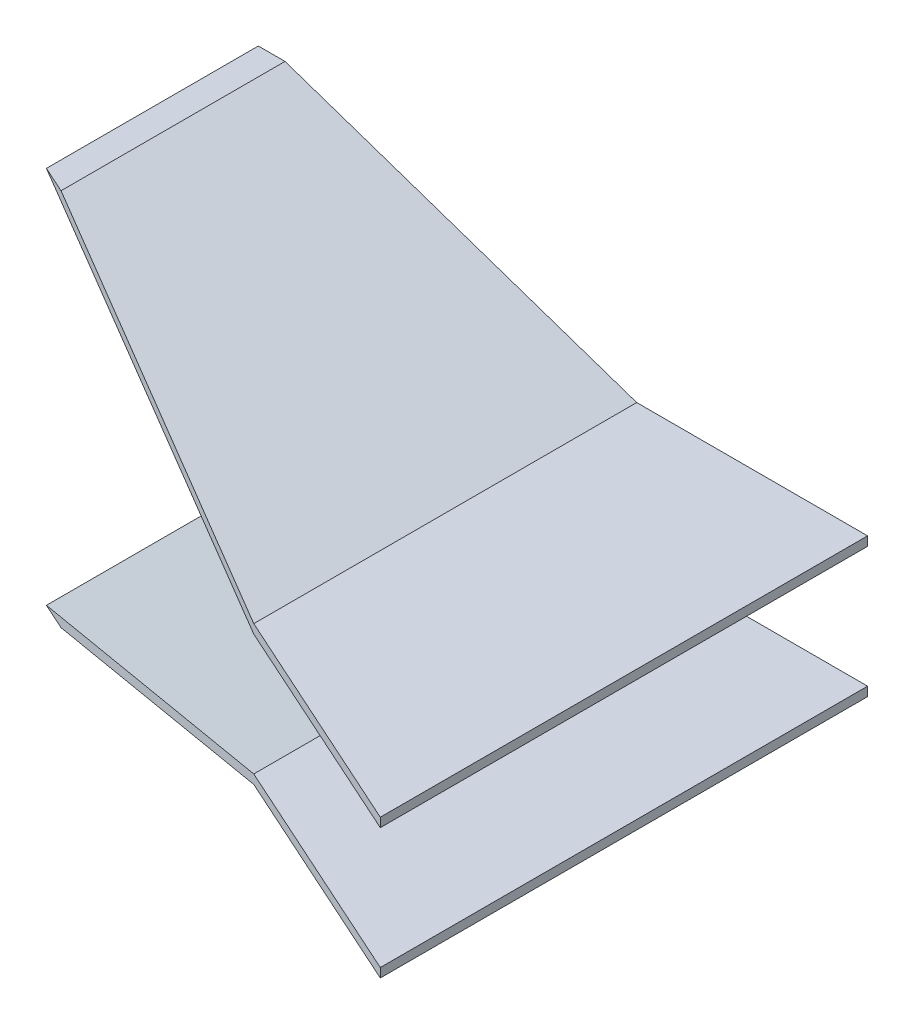
SolidWorks part; units mm, degrees
ref_plane "Plano frontal" through (0, 0, 0) normal (0, 0, 1) x (1, 0, 0)
ref_plane "Plano superior" through (0, 0, 0) normal (0, 1, 0) x (1, 0, 0)
ref_plane "Plano direito" through (0, 0, 0) normal (1, 0, 0) x (0, 0, -1)
sketch "Esboço1" plane through (0, 0, 0) normal (0, 0, 1) x (1, 0, 0)
  line L1 (0, 0) -> (6, 0)
  line L2 (0, 0) -> (0, -250)
  line L3 (0, -250) -> (6, -250)
  line L4 (6, 0) -> (6, -250)
extrude "Ressalto-extrusão1" add sketch "Esboço1" along normal blind 140
sketch "Esboço3" plane through (0, 0, 0) normal (0, 1, 0) x (1, 0, 0)
  line L0 (6, -140) -> (256, -253)
  line L1 (6, -140) -> (256, -140)
  line L2 (256, -140) -> (256, -253)
extrude "Ressalto-extrusão2" add sketch "Esboço3" against normal blind 250 separate body
sketch "Esboço5" plane through (0, 0, 140) normal (0, 0, -1) x (-1, 0, 0)
  line L0 (-256, 0) -> (-256, -250) construction
  line L3 (-256, -85) -> (-6, 0)
  line L8 (-6, -250) -> (-256, -165)
  line L9 (-6, 0) -> (-6, -250)
  line L12 (-256, -165) -> (-256, -85)
extrude "Corte-extrusão2" cut sketch "Esboço5" against normal through all
sketch "Esboço6" plane through (0, 0, 140) normal (0, 0, -1) x (-1, 0, 0)
  line L0 (-256, -85) -> (-256, -79)
  line L1 (-256, -85) -> (-256, 0) construction
  line L3 (-256, -171) -> (-256, -250)
  line L5 (-256, 0) -> (-256, -79)
  line L6 (-256, -250) -> (-256, -165) construction
  line L7 (-256, -250) -> (-6, -250) construction
  line L8 (-256, -79) -> (-23.6471, 0)
  line L9 (-256, -250) -> (-6, -250)
  line L10 (-23.6471, 0) -> (-256, 0)
  line L11 (-256, 0) -> (-6, 0) construction
  line L13 (-256, -171) -> (-23.6471, -250)
  line L15 (-256, -250) -> (-23.6471, -250)
  line M11 (-6, 0) -> (-256, 0)
  line M12 (-256, 0) -> (-256, -85)
  dimension "D1" = 6
  dimension "D2" = 6
extrude "Corte-extrusão3" cut sketch "Esboço6" against normal through all contours L8 M12 M11 | L13 L3 L9
sketch "Esboço7" plane through (6, 0, 0) normal (1, 0, 0) x (0, 0, -1)
  line L0 (-140, -79) -> (-140, 0) construction
  line L1 (0, 0) -> (-140, 0)
  line L2 (0, 0) -> (0, -250)
  line L3 (0, -250) -> (-140, -250)
  line L4 (-140, 0) -> (-140, -250)
sketch "Esboço8" plane through (0, 0, 140) normal (0, 0, -1) x (-1, 0, 0)
  line L0 (-256, -79) -> (-23.6471, 0)
  line L1 (-23.6471, 0) -> (-6, 0)
  line L2 (-6, 0) -> (-6, -250) construction
  line L3 (-6, 0) -> (-256, -85) construction
  line L4 (-6, 0) -> (-256, -85)
  line L5 (-256, -85) -> (-256, -79)
  line L6 (-256, -165) -> (-256, -171)
  line L7 (-256, -171) -> (-23.6471, -250)
  line L8 (-23.6471, -250) -> (-6, -250)
  line L9 (-6, -250) -> (-256, -165)
extrude "Ressalto-extrusão3" add sketch "Esboço8" along normal blind 140
sketch "Esboço9" plane through (6, 0, 0) normal (1, 0, 0) x (0, 0, -1)
extrude "Corte-extrusão4" cut sketch "Esboço7" against normal through all
sketch "Esboço11" plane through (-51.527, 0, 113.9978) normal (-0.4119, 0, 0.9112) x (0.9112, 0, 0.4119)
  line L0 (337.4825, -85) -> (504.8825, -85)
  line L1 (337.4825, -79) -> (504.8825, -79)
  line L2 (337.4825, -85) -> (337.4825, -79) construction
  line L3 (82.4966, 0) -> (337.4825, -79) construction
  line L4 (504.8825, -79) -> (504.8825, -85)
  line L6 (337.4825, -165) -> (504.8825, -165)
  line L8 (337.4825, -171) -> (504.8825, -171)
  line L9 (504.8825, -171) -> (504.8825, -165)
  line L10 (337.4825, -85) -> (201.906, -42.9955)
  line L11 (337.4825, -85) -> (63.1306, 0) construction
  line L12 (201.906, -42.9955) -> (203.6021, -37.521)
  line L13 (203.6021, -37.521) -> (337.4825, -79)
  line L14 (337.4825, -171) -> (181.315, -219.384)
  line L15 (82.4966, -250) -> (337.4825, -171) construction
  line L16 (181.315, -219.384) -> (179.6188, -213.9095)
  line L17 (63.1306, -250) -> (337.4825, -165) construction
  line L18 (179.6188, -213.9095) -> (337.4825, -165)
  line L19 (337.4825, -79) -> (337.4825, -85)
  line L20 (337.4825, -171) -> (337.4825, -165)
sketch "Esboço16" plane through (0, 0, 0) normal (0, 0, -1) x (-1, 0, 0)
  line L2 (-256, -79) -> (-408.5413, -79)
  line L3 (-408.5413, -79) -> (-408.5413, -85)
  line L4 (-408.5413, -85) -> (-256, -85)
  line L6 (-256, -85) -> (-408.5413, -85) construction
  line L7 (-256, -165) -> (-256, -171)
  line L8 (-256, -171) -> (-408.5413, -171)
  line L9 (-408.5413, -171) -> (-408.5413, -165)
  line L10 (-408.5413, -165) -> (-256, -165)
  line L11 (-256, -85) -> (-132.4575, -42.9955) construction
  line L12 (-256, -85) -> (-256, -79)
extrude "Ressalto-extrusão7" add sketch "Esboço16" against normal blind 818
ref_plane "Plano4" through (-51.527, 0, 113.9978) normal (-0.4119, 0, 0.9112) x (0.9112, 0, 0.4119)
sketch "Esboço18" plane through (-51.527, 0, 113.9978) normal (-0.4119, 0, 0.9112) x (0.9112, 0, 0.4119)
  line L1 (-106.1685, 107.1096) -> (769.831, 107.1096)
  line L2 (-106.1685, 107.1096) -> (-106.1685, -311.0849)
  line L3 (-106.1685, -311.0849) -> (769.831, -311.0849)
  line L4 (769.831, 107.1096) -> (769.831, -311.0849)
extrude "Corte-extrusão7" cut sketch "Esboço18" along normal through all
